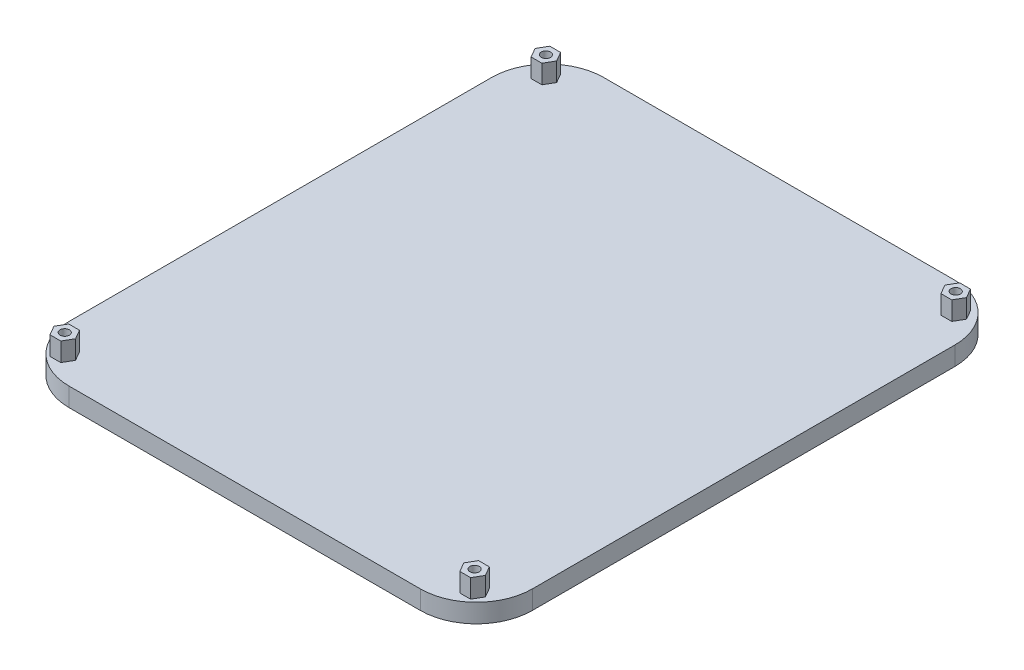
SolidWorks part; units mm, degrees
ref_plane "Front Plane" through (0, 0, 0) normal (0, 0, 1) x (1, 0, 0)
ref_plane "Top Plane" through (0, 0, 0) normal (0, 1, 0) x (1, 0, 0)
ref_plane "Right Plane" through (0, 0, 0) normal (1, 0, 0) x (0, 0, -1)
sketch "Sketch1" plane through (0, 0, 0) normal (0, 1, 0) x (1, 0, 0)
  line L1 (-46.9525, -71.4375) -> (46.9525, -71.4375)
  line L2 (-61.9125, -56.4775) -> (-61.9125, 56.4775)
  line L3 (-46.9525, 71.4375) -> (46.9525, 71.4375)
  line L4 (61.9125, -56.4775) -> (61.9125, 56.4775)
  line L5 (-61.9125, -71.4375) -> (61.9125, 71.4375) construction
  line L6 (-61.9125, 71.4375) -> (61.9125, -71.4375) construction
  arc A0 (46.9525, 71.4375) -> (61.9125, 56.4775) centre (46.9525, 56.4775) cw
  arc A4 (-61.9125, 56.4775) -> (-46.9525, 71.4375) centre (-46.9525, 56.4775) cw
  arc A5 (-46.9525, -71.4375) -> (-61.9125, -56.4775) centre (-46.9525, -56.4775) cw
  arc A6 (46.9525, -71.4375) -> (61.9125, -56.4775) centre (46.9525, -56.4775) ccw
  point P0 (0, 0)
  dimension "D3" = 14.96
  dimension "D5" = 14.96
  dimension "D4" = 14.96
  dimension "D6" = 14.96
  dimension "D1" = 123.825
  dimension "D2" = 142.875
extrude "Floor" add sketch "Sketch1" along normal blind 5
sketch "Sketch2" plane through (0, 5, 0) normal (0, 1, 0) x (1, 0, 0)
  line L0 (46.9525, 71.4375) -> (-46.9525, 71.4375) construction
  line L7 (61.9125, -56.4775) -> (61.9125, 56.4775) construction
  line L44 (-61.9125, 56.4775) -> (-61.9125, -56.4775) construction
  line L45 (-46.9525, -71.4375) -> (46.9525, -71.4375) construction
  line L47 (-56.3709, -62.1125) -> (-57.8143, -64.6125)
  line L48 (-57.8143, -64.6125) -> (-56.3709, -67.1125)
  line L49 (-56.3709, -67.1125) -> (-53.4841, -67.1125)
  line L50 (-53.4841, -67.1125) -> (-52.0407, -64.6125)
  line L51 (-52.0407, -64.6125) -> (-53.4841, -62.1125)
  line L52 (-53.4841, -62.1125) -> (-56.3709, -62.1125)
  line L53 (56.0559, -62.1125) -> (53.1691, -62.1125)
  line L54 (53.1691, -62.1125) -> (51.7257, -64.6125)
  line L55 (51.7257, -64.6125) -> (53.1691, -67.1125)
  line L56 (53.1691, -67.1125) -> (56.0559, -67.1125)
  line L57 (56.0559, -67.1125) -> (57.4993, -64.6125)
  line L58 (57.4993, -64.6125) -> (56.0559, -62.1125)
  line L59 (-56.3709, 66.4775) -> (-57.8143, 63.9775)
  line L60 (-57.8143, 63.9775) -> (-56.3709, 61.4775)
  line L61 (-56.3709, 61.4775) -> (-53.4841, 61.4775)
  line L62 (-53.4841, 61.4775) -> (-52.0407, 63.9775)
  line L63 (-52.0407, 63.9775) -> (-53.4841, 66.4775)
  line L64 (-53.4841, 66.4775) -> (-56.3709, 66.4775)
  line L65 (57.4993, 63.9775) -> (56.0559, 66.4775)
  line L66 (56.0559, 66.4775) -> (53.1691, 66.4775)
  line L67 (53.1691, 66.4775) -> (51.7257, 63.9775)
  line L68 (51.7257, 63.9775) -> (53.1691, 61.4775)
  line L69 (53.1691, 61.4775) -> (56.0559, 61.4775)
  line L70 (56.0559, 61.4775) -> (57.4993, 63.9775)
  circle A0 centre (54.6125, 63.9775) radius 2.5 construction
  circle A7 centre (-54.9275, -64.6125) radius 2.5 construction
  circle A8 centre (54.6125, -64.6125) radius 2.5 construction
  circle A9 centre (-54.9275, 63.9775) radius 2.5 construction
  circle A10 centre (54.6125, 63.9775) radius 1.25
  circle A11 centre (-54.9275, 63.9775) radius 1.25
  circle A12 centre (-54.9275, -64.6125) radius 1.25
  circle A13 centre (54.6125, -64.6125) radius 1.25
  dimension "D4" = 5
  dimension "D5" = 5
  dimension "D6" = 5
  dimension "D2" = 5
  dimension "D3" = 7.46
  dimension "D14" = 2.5
  dimension "D15" = 2.5
  dimension "D16" = 2.5
  dimension "D17" = 2.5
  dimension "D7" = 6.985
  dimension "D8" = 7.46
  dimension "D9" = 6.985
  dimension "D10" = 6.825
  dimension "D11" = 7.3
  dimension "D12" = 6.825
  dimension "D13" = 7.3
extrude "Boss-Extrude1" add sketch "Sketch2" along normal blind 5
